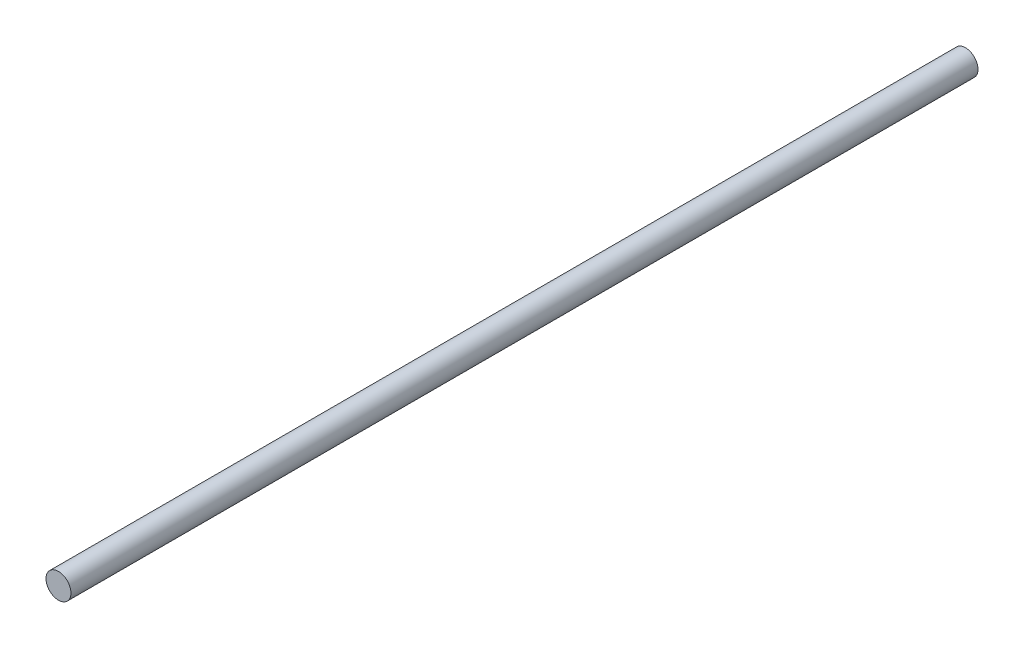
SolidWorks part; units mm, degrees
ref_plane "Ön Düzlem" through (0, 0, 0) normal (0, 0, 1) x (1, 0, 0)
ref_plane "Üst Düzlem" through (0, 0, 0) normal (0, 1, 0) x (1, 0, 0)
ref_plane "Sağ Düzlem" through (0, 0, 0) normal (1, 0, 0) x (0, 0, -1)
sketch "Çizim1" plane through (0, 0, 0) normal (0, 0, 1) x (1, 0, 0)
  circle A0 centre (0, 0) radius 6
  dimension "D1" = 12
extrude "Yükseklik-Ekstrüzyon1" add sketch "Çizim1" along normal mid plane 436
